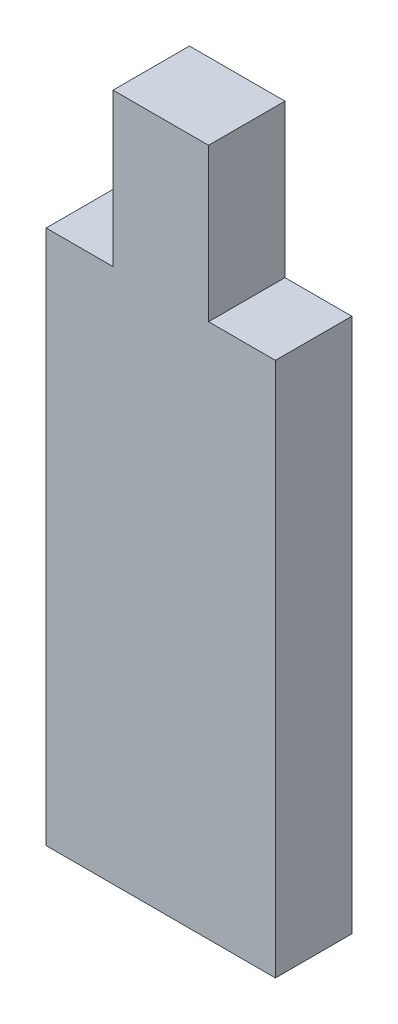
SolidWorks part; units mm, degrees
ref_plane "Front Plane" through (0, 0, 0) normal (0, 0, 1) x (1, 0, 0)
ref_plane "Top Plane" through (0, 0, 0) normal (0, 1, 0) x (1, 0, 0)
ref_plane "Right Plane" through (0, 0, 0) normal (1, 0, 0) x (0, 0, -1)
sketch "Sketch1" plane through (0, 0, 0) normal (0, 0, 1) x (1, 0, 0)
  line L0 (0, 0) -> (0, 28)
  line L1 (0, 28) -> (3.5, 28)
  line L2 (3.5, 28) -> (3.5, 36)
  line L3 (3.5, 36) -> (8.5, 36)
  line L4 (8.5, 36) -> (8.5, 28)
  line L5 (8.5, 28) -> (12, 28)
  line L6 (12, 28) -> (12, 0)
  line L7 (12, 0) -> (0, 0)
  dimension "D1" = 28
  dimension "D2" = 8
  dimension "D3" = 5
  dimension "D4" = 12
extrude "Boss-Extrude1" add sketch "Sketch1" along normal blind 4
